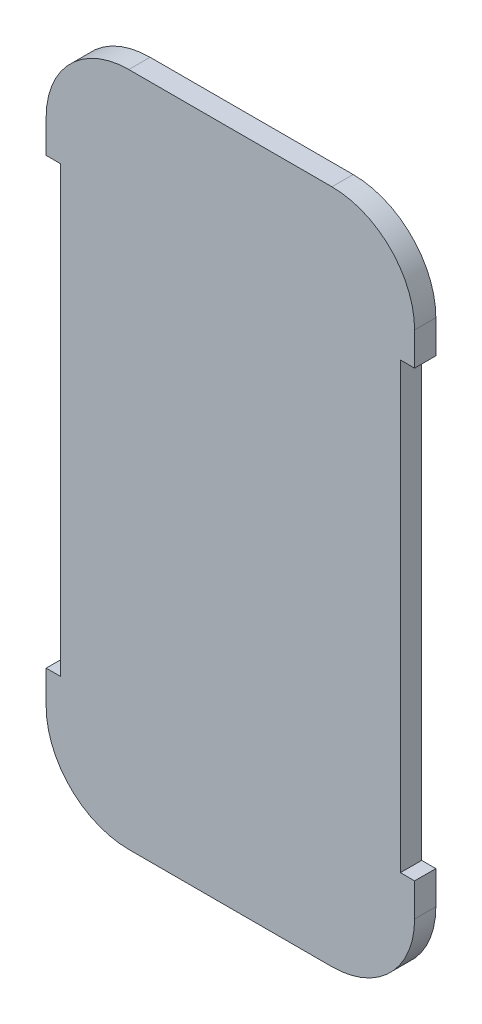
SolidWorks part; units mm, degrees
material "ABS"
ref_plane "Front Plane" through (0, 0, 0) normal (0, 0, 1) x (1, 0, 0)
ref_plane "Top Plane" through (0, 0, 0) normal (0, 1, 0) x (1, 0, 0)
ref_plane "Right Plane" through (0, 0, 0) normal (1, 0, 0) x (0, 0, -1)
ref_plane "Plane1" through (0, 0, 4.2) normal (0, 0, -1) x (-1, 0, 0)
sketch "Sketch1" plane through (0, 0, 4.2) normal (0, 0, -1) x (-1, 0, 0)
  line L0 (-55.7, 309.3) -> (-64.3, 309.3)
  line L1 (-67.8, 305.8) -> (-67.8, 304.4)
  line L2 (-67.8, 304.4) -> (-67.2, 304.4)
  line L3 (-67.2, 304.4) -> (-67.2, 285.6)
  line L4 (-67.2, 285.6) -> (-67.8, 285.6)
  line L5 (-67.8, 285.6) -> (-67.8, 284.2)
  line L6 (-64.3, 280.7) -> (-55.7, 280.7)
  line L7 (-52.2, 284.2) -> (-52.2, 285.6)
  line L8 (-52.2, 285.6) -> (-52.8, 285.6)
  line L9 (-52.8, 285.6) -> (-52.8, 304.4)
  line L10 (-52.8, 304.4) -> (-52.2, 304.4)
  line L11 (-52.2, 304.4) -> (-52.2, 305.8)
  arc A0 (-64.3, 309.3) -> (-67.8, 305.8) centre (-64.3, 305.8) ccw
  arc A1 (-67.8, 284.2) -> (-64.3, 280.7) centre (-64.3, 284.2) ccw
  arc A2 (-55.7, 280.7) -> (-52.2, 284.2) centre (-55.7, 284.2) ccw
  arc A3 (-52.2, 305.8) -> (-55.7, 309.3) centre (-55.7, 305.8) ccw
extrude "Extrude1" add sketch "Sketch1" against normal blind 0.9
